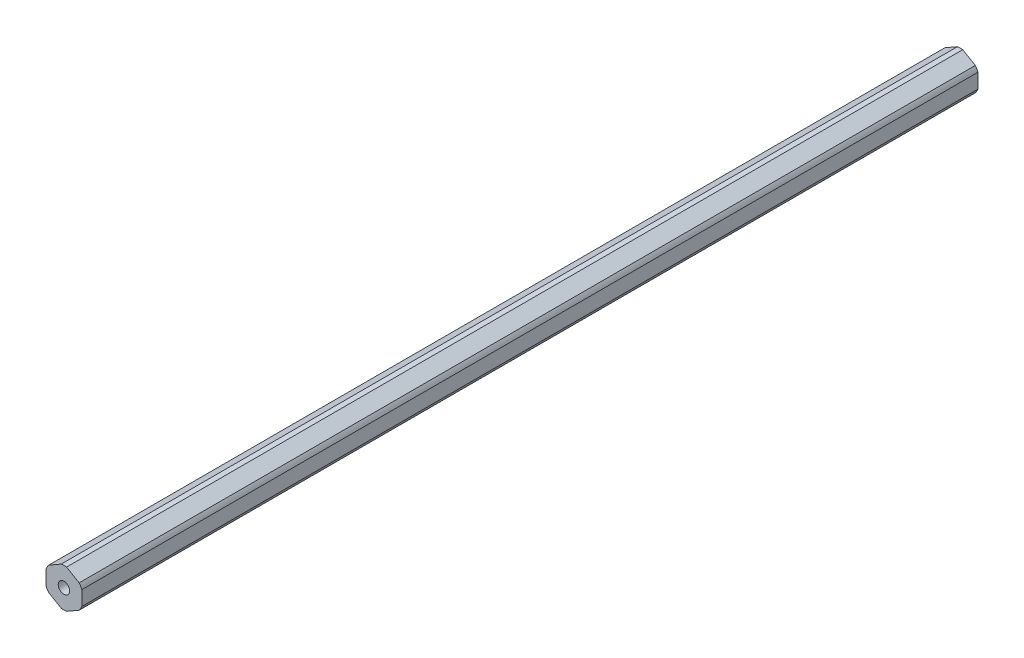
SolidWorks part; units mm, degrees
material "7075-T6 (SN)"
ref_plane "Front Plane" through (0, 0, 0) normal (0, 0, 1) x (1, 0, 0)
ref_plane "Top Plane" through (0, 0, 0) normal (0, 1, 0) x (1, 0, 0)
ref_plane "Right Plane" through (0, 0, 0) normal (1, 0, 0) x (0, 0, -1)
sketch "Sketch1" plane through (0, 0, 0) normal (0, 0, 1) x (1, 0, 0)
  line L7 (6.35, 3.6662) -> (0, 7.3323)
  line L8 (0, 7.3323) -> (-6.35, 3.6662)
  line L9 (-6.35, 3.6662) -> (-6.35, -3.6662)
  line L10 (-6.35, -3.6662) -> (0, -7.3323)
  line L11 (0, -7.3323) -> (6.35, -3.6662)
  line L12 (6.35, -3.6662) -> (6.35, 3.6662)
  circle A0 centre (0, 0) radius 6.35 construction
  circle A2 centre (0, 0) radius 6.858
  dimension "D1" = 12.7
  dimension "D2" = 13.716
extrude "Boss-Extrude1" add sketch "Sketch1" along normal mid plane 317.7032 contours L12 A2 L7 L8 L9 L10 L11
sketch "Sketch2" plane through (0, 0, 158.8516) normal (0, 0, 1) x (1, 0, 0)
  circle A0 centre (0, 0) radius 2.0193
  dimension "D1" = 4.0386
extrude "Cut-Extrude1" [suppressed] cut sketch "Sketch2" against normal through all
hole_wizard "#10-32 Tapped Hole1" positions "3DSketch1" profile "Sketch5" tap size "#10-32" standard "ANSI Inch"
sketch3d "3DSketch1"
  line L0 (0, 0, 158.8516) -> (0, 0, -158.8516) construction
  point P0 (0, 0, -158.8516)
  point P4 (0, 0, 158.8516)
sketch "Sketch5" plane through (0, 0, -158.8516) normal (1, 0, 0) x (0, 1, 0)
  line L0 (0, 0) -> (0, 13.2428)
  line L1 (0, 13.2428) -> (2.0193, 12.0294)
  line L2 (2.0193, 12.0294) -> (2.0193, 0)
  line L5 (2.0193, 0) -> (0, 0)
  line L10 (0, 13.2428) -> (-2.0193, 12.0294) construction
  line L11 (0, -6.35) -> (0, 107.95) construction
  dimension "Tap Drill Dia." = 4.0386
  dimension "Tap Drill Depth" = 12.0294
  dimension "Drill Angle" = 118
cosmetic thread "Hole Thread1" parameters "D1"=9.652, "D2"=4.826
cosmetic thread "Hole Thread2" parameters "D1"=9.652, "D2"=4.826
